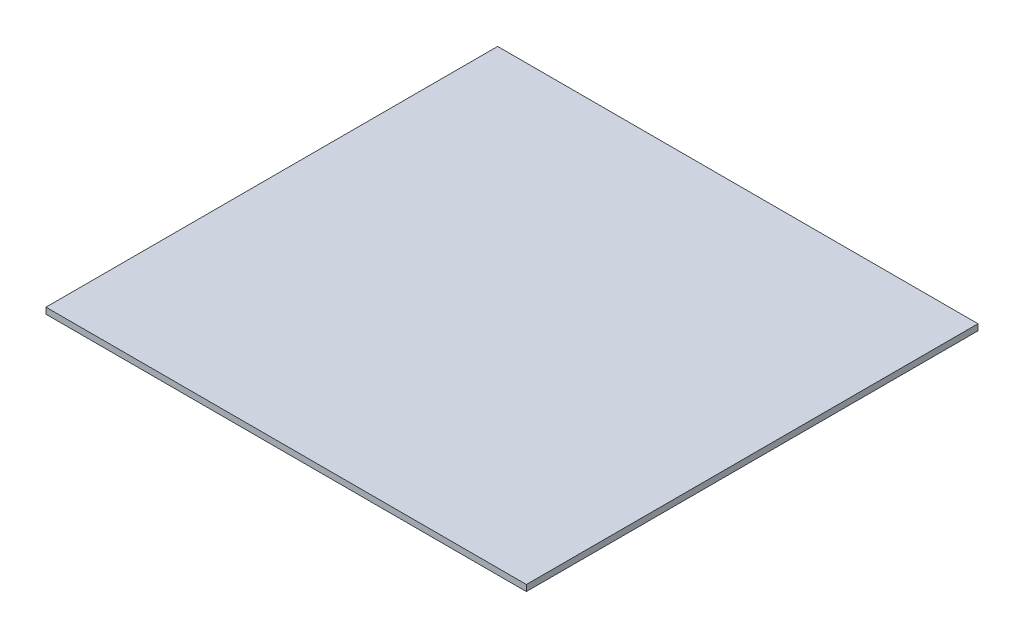
SolidWorks part; units mm, degrees
ref_plane "Front Plane" through (0, 0, 0) normal (0, 0, 1) x (1, 0, 0)
ref_plane "Top Plane" through (0, 0, 0) normal (0, 1, 0) x (1, 0, 0)
ref_plane "Right Plane" through (0, 0, 0) normal (1, 0, 0) x (0, 0, -1)
sketch "Sketch1" plane through (0, 0, 0) normal (0, 1, 0) x (1, 0, 0)
  line L1 (-58.5, 55) -> (58.5, 55)
  line L2 (-58.5, 55) -> (-58.5, -55)
  line L3 (-58.5, -55) -> (58.5, -55)
  line L4 (58.5, 55) -> (58.5, -55)
  line L5 (-58.5, 55) -> (58.5, -55) construction
  line L6 (-58.5, -55) -> (58.5, 55) construction
  point P0 (0, 0)
  dimension "D1" = 117
  dimension "D2" = 110
extrude "Boss-Extrude1" add sketch "Sketch1" along normal blind 1.5
